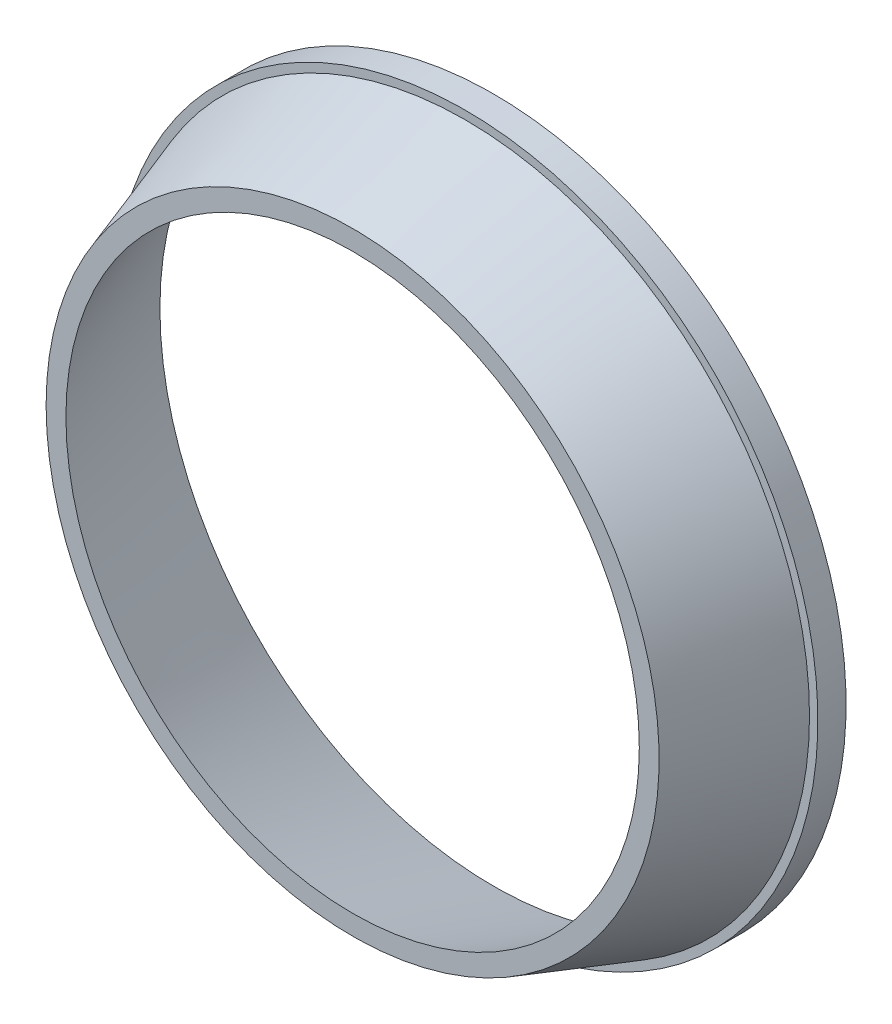
SolidWorks part; units mm, degrees
ref_plane "Front Plane" through (0, 0, 0) normal (0, 0, 1) x (1, 0, 0)
ref_plane "Top Plane" through (0, 0, 0) normal (0, 1, 0) x (1, 0, 0)
ref_plane "Right Plane" through (0, 0, 0) normal (1, 0, 0) x (0, 0, -1)
sketch "Sketch1" plane through (0, 0, 0) normal (0, 1, 0) x (1, 0, 0)
  line L3 (37.5, 0) -> (37.5, -3)
  line L11 (35.5, 0) -> (37.5, 0)
  line L13 (30.5, -15) -> (35.5, 0)
  line L14 (37.5, 0) -> (0, 0)
  line L15 (0, 0) -> (0, -15)
  line L16 (0, -15) -> (30.5, -15)
  line L17 (30.5, -15) -> (32.6082, -15)
  line L18 (32.6082, -15) -> (36.6082, -3)
  line L19 (37.5, -3) -> (36.6082, -3)
  line L21 (32.3974, -15.6325) -> (37.3974, -0.6325) construction
  dimension "D1" = 2
revolve "Revolve1" add sketch "Sketch1" angle 360 about L15
